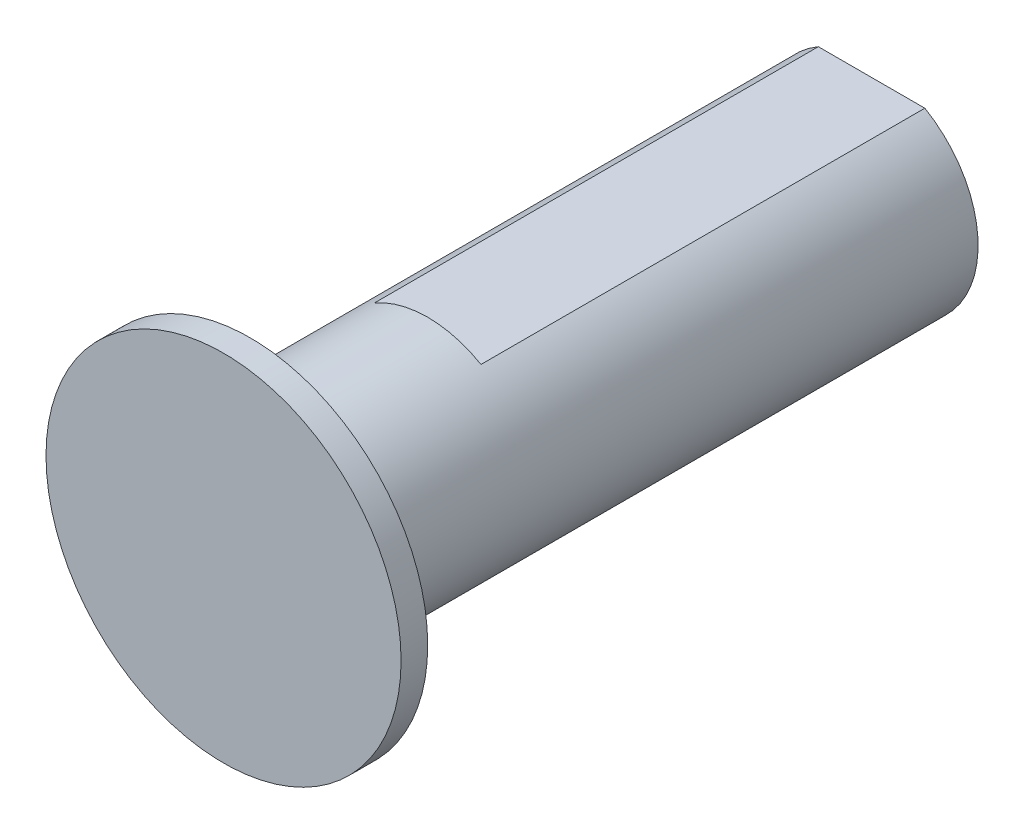
SolidWorks part; units mm, degrees
material "6061 Alloy"
ref_plane "Front Plane" through (0, 0, 0) normal (0, 0, 1) x (1, 0, 0)
ref_plane "Top Plane" through (0, 0, 0) normal (0, 1, 0) x (1, 0, 0)
ref_plane "Right Plane" through (0, 0, 0) normal (1, 0, 0) x (0, 0, -1)
sketch "Sketch1" plane through (0, 0, 0) normal (0, 0, 1) x (1, 0, 0)
  line L0 (-3, 5.1962) -> (3, 5.1962)
  circle A0 centre (0, 0) radius 6
  dimension "D1" = 12
  dimension "D2" = 6
extrude "Boss-Extrude1" add sketch "Sketch1" along normal blind 35 contours A0
sketch "Sketch2" plane through (0, 0, 0) normal (0, 0, -1) x (-1, 0, 0)
  line L0 (-3, 5.1962) -> (3, 5.1962)
  circle A1 centre (0, 0) radius 6 construction
  circle A2 centre (0, 0) radius 6
  circle M3 centre (0, 0) radius 6
  dimension "D1" = 6
extrude "Cut-Extrude1" cut sketch "Sketch2" against normal blind 25 contours L0 M3
sketch "Sketch3" plane through (0, 0, 35) normal (0, 0, 1) x (1, 0, 0)
  circle A0 centre (0, 0) radius 10
  dimension "D1" = 20
extrude "Boss-Extrude2" add sketch "Sketch3" along normal blind 1.5
